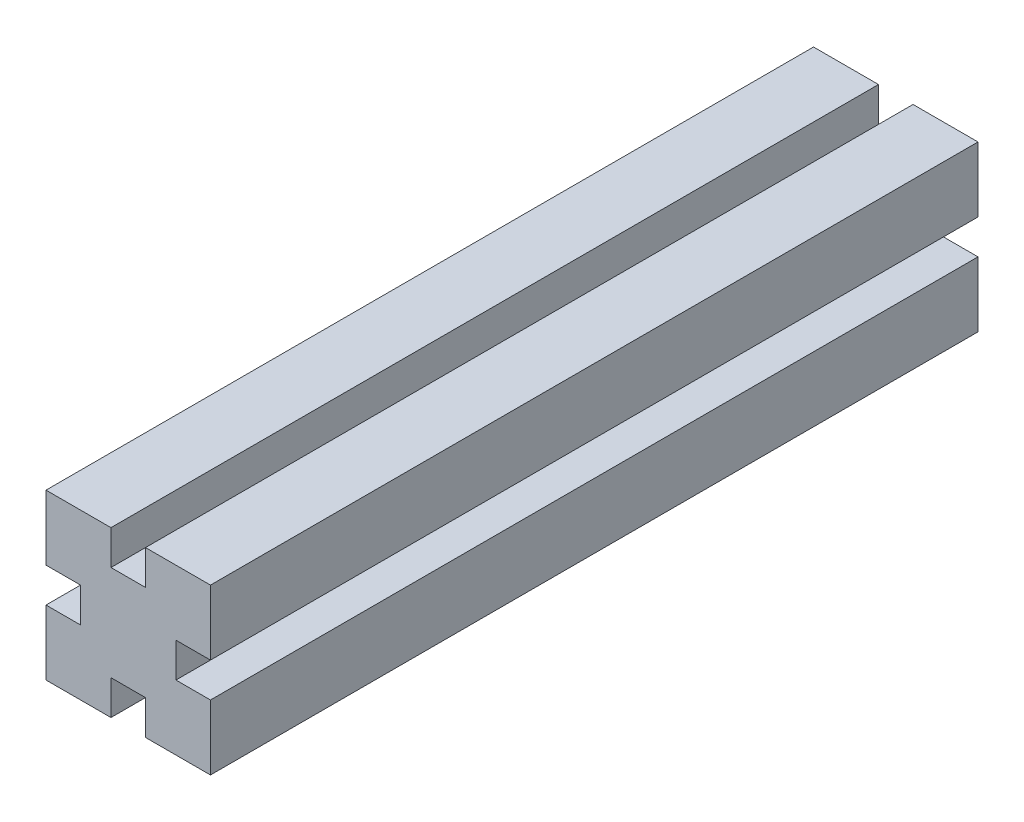
SolidWorks part; units mm, degrees
ref_plane "Front Plane" through (0, 0, 0) normal (0, 0, 1) x (1, 0, 0)
ref_plane "Top Plane" through (0, 0, 0) normal (0, 1, 0) x (1, 0, 0)
ref_plane "Right Plane" through (0, 0, 0) normal (1, 0, 0) x (0, 0, -1)
sketch "Sketch1" plane through (0, 0, 0) normal (0, 0, 1) x (1, 0, 0)
  line L0 (-19.05, -19.05) -> (-4, -19.05)
  line L1 (-4, -19.05) -> (-4, -11.05)
  line L2 (-4, -11.05) -> (4, -11.05)
  line L3 (4, -11.05) -> (4, -19.05)
  line L4 (4, -19.05) -> (19.05, -19.05)
  line L5 (19.05, -19.05) -> (19.05, -4)
  line L6 (19.05, -4) -> (11.05, -4)
  line L7 (11.05, -4) -> (11.05, 4)
  line L8 (11.05, 4) -> (19.05, 4)
  line L9 (19.05, 4) -> (19.05, 19.05)
  line L10 (19.05, 19.05) -> (4, 19.05)
  line L11 (4, 19.05) -> (4, 11.05)
  line L12 (4, 11.05) -> (-4, 11.05)
  line L13 (-4, 11.05) -> (-4, 19.05)
  line L14 (-4, 19.05) -> (-19.05, 19.05)
  line L15 (-19.05, 19.05) -> (-19.05, 4)
  line L16 (-19.05, 4) -> (-11.05, 4)
  line L17 (-11.05, 4) -> (-11.05, -4)
  line L18 (-11.05, -4) -> (-19.05, -4)
  line L19 (-19.05, -4) -> (-19.05, -19.05)
extrude "Profile" add sketch "Sketch1" along normal blind 177.8
equation "\"length\" = 177.8mm"
equation "\"D1@Profile\" = \"length\""
